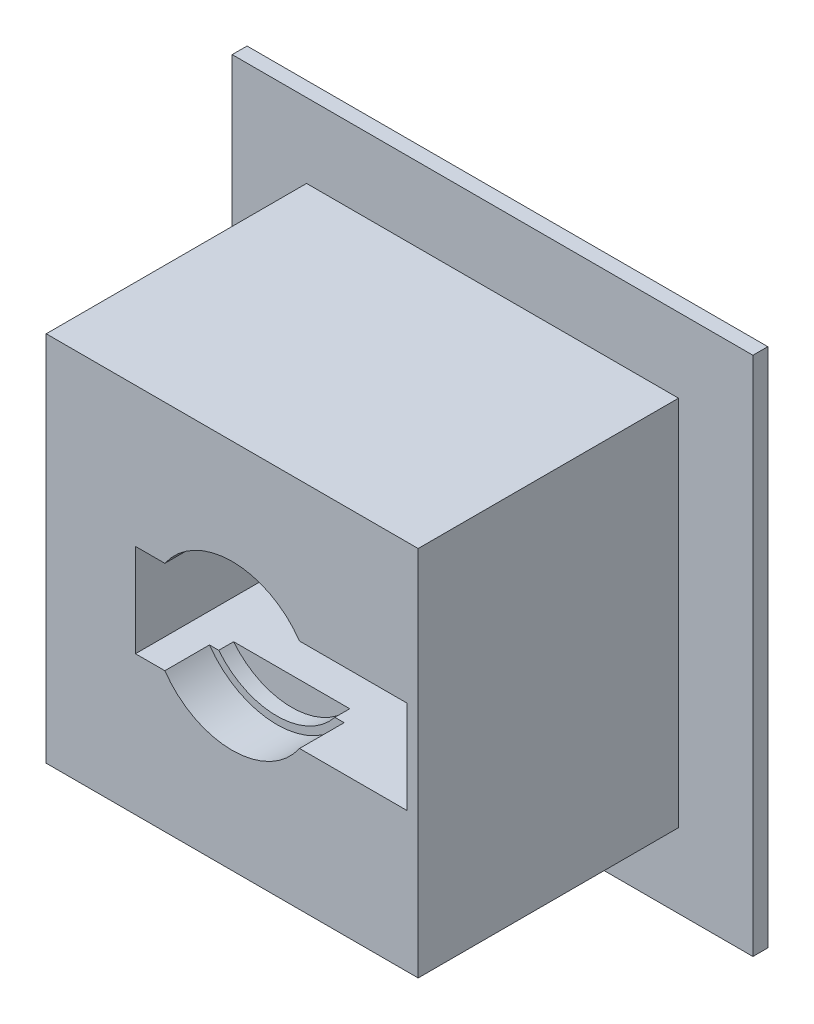
SolidWorks part; units mm, degrees
ref_plane "Front Plane" through (0, 0, 0) normal (0, 0, 1) x (1, 0, 0)
ref_plane "Top Plane" through (0, 0, 0) normal (0, 1, 0) x (1, 0, 0)
ref_plane "Right Plane" through (0, 0, 0) normal (1, 0, 0) x (0, 0, -1)
sketch "Sketch1" plane through (0, 0, 0) normal (0, 0, 1) x (1, 0, 0)
  line L1 (70, -70) -> (0, -70)
  line L2 (70, -70) -> (70, 0)
  line L3 (70, 0) -> (0, 0)
  line L4 (0, -70) -> (0, 0)
  dimension "D1" = 70
  dimension "D2" = 70
extrude "Boss-Extrude1" add sketch "Sketch1" along normal blind 2
sketch "Sketch2" plane through (0, 0, 2) normal (0, 0, 1) x (1, 0, 0)
  line L0 (35, -70) -> (35, 0) construction
  line L1 (0, -70) -> (70, -70) construction
  line L2 (70, 0) -> (0, 0) construction
  line L4 (0, 0) -> (0, -70) construction
  line L5 (0, -35) -> (70, -35) construction
  line L6 (70, -70) -> (70, 0) construction
  line L7 (60, -10) -> (10, -10)
  line L8 (60, -10) -> (60, -60)
  line L9 (60, -60) -> (10, -60)
  line L10 (10, -10) -> (10, -60)
  line L11 (60, -10) -> (10, -60) construction
  line L12 (60, -60) -> (10, -10) construction
  point P6 (35, -35)
  dimension "D1" = 50
extrude "Boss-Extrude2" add sketch "Sketch2" along normal blind 35
sketch "Sketch3" plane through (0, 0, 37) normal (0, 0, 1) x (1, 0, 0)
  line L0 (35, -60) -> (35, -10) construction
  line L5 (10, -60) -> (60, -60) construction
  line L6 (60, -10) -> (10, -10) construction
  circle A0 centre (35, -35) radius 11
  dimension "D1" = 22
extrude "Cut-Extrude1" cut sketch "Sketch3" against normal blind 6
sketch "Sketch4" plane through (0, 0, 31) normal (0, 0, 1) x (1, 0, 0)
  circle A0 centre (35, -35) radius 10
  dimension "D1" = 20
extrude "Cut-Extrude2" cut sketch "Sketch4" against normal blind 2
sketch "Sketch5" plane through (0, 0, 37) normal (0, 0, 1) x (1, 0, 0)
  line L0 (35, -41.25) -> (35, -35) construction
  line L1 (53.5, -41.25) -> (27, -41.25)
  line L2 (53.5, -41.25) -> (53.5, -28.75)
  line L3 (53.5, -28.75) -> (27, -28.75)
  line L4 (27, -41.25) -> (27, -28.75)
  line L5 (27, -35) -> (53.5, -35) construction
  line L6 (35, -35) -> (35, -28.75) construction
  dimension "D1" = 26.5
  dimension "D2" = 12.5
  dimension "D3" = 18.5
extrude "Cut-Extrude3" cut sketch "Sketch5" against normal through all
sketch "Sketch7" plane through (53.5, 0, 0) normal (-1, 0, 0) x (0, 0, 1)
  line L0 (0, -35) -> (5, -35) construction
  line L1 (0, -37.5115) -> (5, -37.5115)
  line L2 (0, -37.5115) -> (0, -32.4885)
  line L3 (0, -32.4885) -> (5, -32.4885)
  line L4 (5, -37.5115) -> (5, -32.4885)
  line L5 (0, -41.25) -> (0, -28.75) construction
  dimension "D1" = 5.0231
  dimension "D2" = 5
extrude "Cut-Extrude4" cut sketch "Sketch7" along normal through all
sketch "Sketch8" plane through (0, 0, 37) normal (0, 0, 1) x (1, 0, 0)
  line L1 (53.5, -41.25) -> (58.5, -41.25)
  line L2 (53.5, -41.25) -> (53.5, -28.75)
  line L3 (53.5, -28.75) -> (58.5, -28.75)
  line L4 (58.5, -41.25) -> (58.5, -28.75)
  line L5 (22, -41.25) -> (27, -41.25)
  line L6 (22, -41.25) -> (22, -28.75)
  line L7 (22, -28.75) -> (27, -28.75)
  line L8 (27, -41.25) -> (27, -28.75)
  dimension "D1" = 5
extrude "Cut-Extrude5" cut sketch "Sketch8" against normal offset from surface (18 mm away) 12 up to face at (31.4052, -35, 31)
